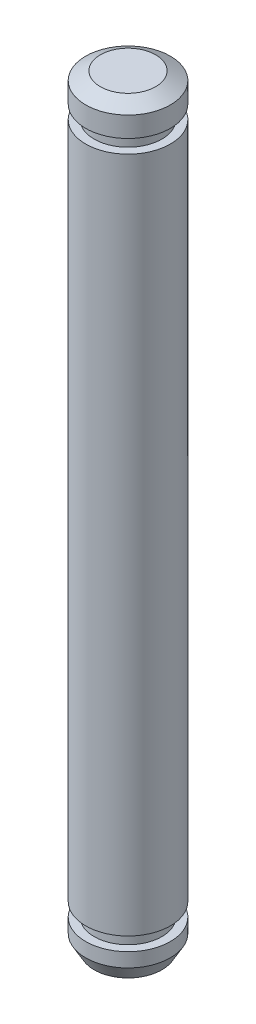
SolidWorks part; units mm, degrees
ref_plane "前视基准面" through (0, 0, 0) normal (0, 0, 1) x (1, 0, 0)
ref_plane "上视基准面" through (0, 0, 0) normal (0, 1, 0) x (1, 0, 0)
ref_plane "右视基准面" through (0, 0, 0) normal (1, 0, 0) x (0, 0, -1)
other "Configuration Table"
sketch "草图1" plane through (0, 0, 0) normal (0, 1, 0) x (1, 0, 0)
  circle A0 centre (0, 0) radius 2.5
  dimension "D1" = 5
extrude "凸台-拉伸2" add sketch "草图1" along normal blind 22.5
ref_plane "基准面1" through (0, 20, 0) normal (0, 1, 0) x (1, 0, 0)
sketch "草图2" plane through (0, 20, 0) normal (0, 1, 0) x (1, 0, 0)
  circle A0 centre (0, 0) radius 2
  circle A1 centre (0, 0) radius 2.5
  dimension "D1" = 4
  dimension "D2" = 5
extrude "切除-拉伸1" cut sketch "草图2" along normal blind 0.8
mirror "镜向3" about plane through (0, 0, 0) normal (0, 1, 0) of "凸台-拉伸2"
mirror "镜向5" about plane through (0, 0, 0) normal (0, 1, 0) of "切除-拉伸1"
chamfer "倒角3" distance 0.5 angle 60 2 edges at (0, -22.5, 2.5) (0, 22.5, 2.5)
